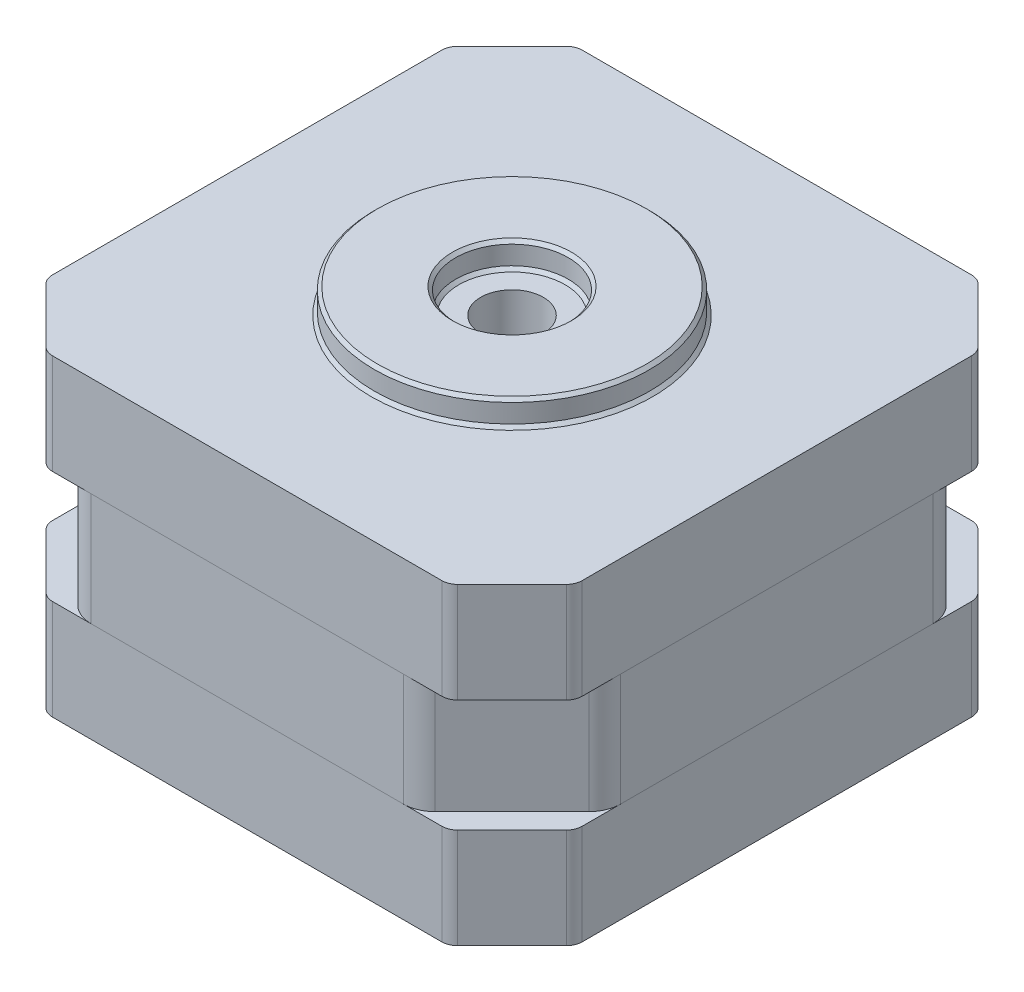
SolidWorks part; units mm, degrees
ref_plane "Front Plane" through (0, 0, 0) normal (0, 0, 1) x (1, 0, 0)
ref_plane "Top Plane" through (0, 0, 0) normal (0, 1, 0) x (1, 0, 0)
ref_plane "Right Plane" through (0, 0, 0) normal (1, 0, 0) x (0, 0, -1)
sketch "Sketch1" plane through (0, 0, 0) normal (0, 1, 0) x (1, 0, 0)
  line L1 (-21.15, 21.15) -> (21.15, 21.15)
  line L2 (-21.15, 21.15) -> (-21.15, -21.15)
  line L3 (-21.15, -21.15) -> (21.15, -21.15)
  line L4 (21.15, 21.15) -> (21.15, -21.15)
  line L5 (-21.15, 21.15) -> (21.15, -21.15) construction
  line L6 (-21.15, -21.15) -> (21.15, 21.15) construction
  point P0 (0, 0)
  dimension "D1" = 42.3
extrude "Boss-Extrude1" add sketch "Sketch1" along normal blind 8.001
chamfer "Chamfer1" distance 5.08 angle 45 4 edges at (-21.15, 4.0005, 21.15) (-21.15, 4.0005, -21.15) (21.15, 4.0005, -21.15) (21.15, 4.0005, 21.15)
sketch "Sketch2" plane through (0, 8.001, 0) normal (0, 1, 0) x (1, 0, 0)
  line L0 (16.07, 21.15) -> (-16.07, 21.15) construction
  line L1 (-21.15, -21.15) -> (21.15, -21.15)
  line L2 (-21.15, -21.15) -> (-21.15, 21.15)
  line L3 (-21.15, 21.15) -> (21.15, 21.15)
  line L4 (21.15, -21.15) -> (21.15, 21.15)
  line L5 (-21.15, -21.15) -> (21.15, 21.15) construction
  line L6 (-21.15, 21.15) -> (21.15, -21.15) construction
  line L7 (21.15, -16.07) -> (21.15, 16.07) construction
  point P0 (0, 0)
extrude "Boss-Extrude2" add sketch "Sketch2" along normal blind 8.9916 separate body
chamfer "Chamfer3" distance 7.62 angle 45 4 edges at (-21.15, 12.4968, -21.15) (-21.15, 12.4968, 21.15) (21.15, 12.4968, 21.15) (21.15, 12.4968, -21.15)
fillet "Fillet1" radius 2.54 8 edges at (-21.15, 12.4968, -13.53) (-13.53, 12.4968, -21.15) (13.53, 12.4968, -21.15) (21.15, 12.4968, -13.53) (21.15, 12.4968, 13.53) (13.53, 12.4968, 21.15) (-13.53, 12.4968, 21.15) (-21.15, 12.4968, 13.53)
fillet "Fillet2" radius 1.27 8 edges at (-21.15, 4.0005, -16.07) (-16.07, 4.0005, -21.15) (16.07, 4.0005, -21.15) (21.15, 4.0005, -16.07) (21.15, 4.0005, 16.07) (16.07, 4.0005, 21.15) (-16.07, 4.0005, 21.15) (-21.15, 4.0005, 16.07)
sketch "Sketch3" plane through (0, 16.9926, 0) normal (0, 1, 0) x (1, 0, 0)
  line L0 (21.15, -12.4779) -> (21.15, 12.4779) construction
  line L1 (-21.15, 21.15) -> (21.15, 21.15)
  line L2 (-21.15, 21.15) -> (-21.15, -21.15)
  line L3 (-21.15, -21.15) -> (21.15, -21.15)
  line L4 (21.15, 21.15) -> (21.15, -21.15)
  line L5 (-21.15, 21.15) -> (21.15, -21.15) construction
  line L6 (-21.15, -21.15) -> (21.15, 21.15) construction
  line L7 (12.4779, 21.15) -> (-12.4779, 21.15) construction
  point P0 (0, 0)
extrude "Boss-Extrude3" add sketch "Sketch3" along normal blind 8.001 separate body
chamfer "Chamfer4" distance 5.08 angle 45 4 edges at (-21.15, 20.9931, 21.15) (-21.15, 20.9931, -21.15) (21.15, 20.9931, -21.15) (21.15, 20.9931, 21.15)
fillet "Fillet3" radius 1.27 8 edges at (-21.15, 20.9931, -16.07) (-16.07, 20.9931, -21.15) (16.07, 20.9931, -21.15) (21.15, 20.9931, -16.07) (21.15, 20.9931, 16.07) (16.07, 20.9931, 21.15) (-16.07, 20.9931, 21.15) (-21.15, 20.9931, 16.07)
sketch "Sketch4" plane through (0, 24.9936, 0) normal (0, 1, 0) x (1, 0, 0)
  circle A0 centre (0, 0) radius 10.9982
  circle A1 centre (0, 0) radius 4.4958
  dimension "D1" = 21.9964
  dimension "D2" = 8.9916
extrude "Boss-Extrude4" add sketch "Sketch4" along normal blind 2
chamfer "Chamfer5" distance 0.254 angle 45 4 edges at (0, 26.9936, 10.9982) (0, 24.9936, 10.9982) (0, 24.9936, 4.4958) (0, 26.9936, 4.4958)
sketch "Sketch5" plane through (0, 24.9936, 0) normal (0, 1, 0) x (1, 0, 0)
  circle A0 centre (0, 0) radius 2.5019
  dimension "D1" = 5.0038
extrude "Cut-Extrude1" cut sketch "Sketch5" against normal blind 12.7
